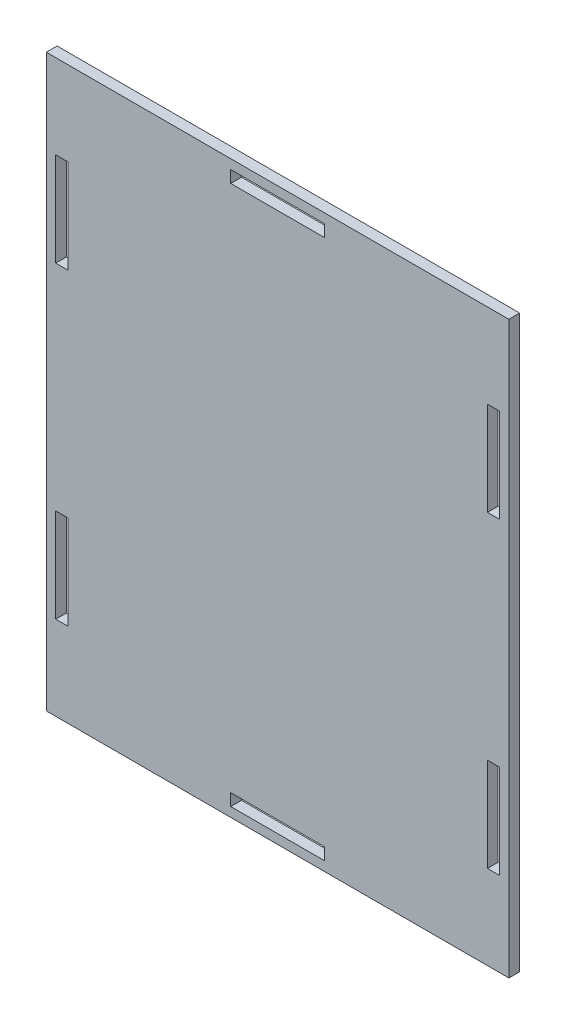
SolidWorks part; units mm, degrees
ref_plane "Спереди" through (0, 0, 0) normal (0, 0, 1) x (1, 0, 0)
ref_plane "Сверху" through (0, 0, 0) normal (0, 1, 0) x (1, 0, 0)
ref_plane "Справа" through (0, 0, 0) normal (1, 0, 0) x (0, 0, -1)
sketch "Эскиз1" plane through (0, 0, 0) normal (0, 0, 1) x (1, 0, 0)
  line L0 (75, 0) -> (75, 75.0147) construction
  line L1 (0, 0) -> (150, 0)
  line L2 (0, 0) -> (0, 185)
  line L3 (0, 185) -> (150, 185)
  line L4 (150, 0) -> (150, 185)
  line L5 (3.05, 57.7) -> (6.95, 57.7)
  line L6 (3.05, 57.7) -> (3.05, 27.3)
  line L7 (3.05, 27.3) -> (6.95, 27.3)
  line L8 (6.95, 57.7) -> (6.95, 27.3)
  line L9 (3.05, 157.7) -> (6.95, 157.7)
  line L10 (3.05, 157.7) -> (3.05, 127.3)
  line L11 (3.05, 127.3) -> (6.95, 127.3)
  line L12 (6.95, 157.7) -> (6.95, 127.3)
  line L13 (5, 127.3) -> (5, 157.7) construction
  line L14 (3.05, 142.5) -> (6.95, 142.5) construction
  line L15 (5, 27.3) -> (5, 57.7) construction
  line L16 (3.05, 42.5) -> (6.95, 42.5) construction
  line L17 (0, 92.5) -> (87.9733, 92.5) construction
  line L18 (146.95, 27.3) -> (143.05, 27.3)
  line L19 (143.05, 57.7) -> (143.05, 27.3)
  line L20 (146.95, 57.7) -> (143.05, 57.7)
  line L21 (146.95, 57.7) -> (146.95, 27.3)
  line L22 (146.95, 127.3) -> (143.05, 127.3)
  line L23 (143.05, 157.7) -> (143.05, 127.3)
  line L24 (146.95, 157.7) -> (143.05, 157.7)
  line L25 (146.95, 157.7) -> (146.95, 127.3)
  line L26 (75, 185) -> (75, 180) construction
  line L27 (59.8, 6.95) -> (90.2, 6.95)
  line L28 (59.8, 181.95) -> (90.2, 181.95)
  line L29 (59.8, 181.95) -> (59.8, 178.05)
  line L30 (59.8, 178.05) -> (90.2, 178.05)
  line L31 (90.2, 181.95) -> (90.2, 178.05)
  line L32 (59.8, 181.95) -> (90.2, 178.05) construction
  line L33 (59.8, 178.05) -> (90.2, 181.95) construction
  line L34 (90.2, 3.05) -> (90.2, 6.95)
  line L35 (59.8, 3.05) -> (90.2, 3.05)
  line L36 (59.8, 3.05) -> (59.8, 6.95)
  point P35 (75, 180)
  dimension "D1" = 185
  dimension "D2" = 150
  dimension "D3" = 30.4
  dimension "D4" = 3.9
  dimension "D5" = 5
  dimension "D6" = 30.4
  dimension "D7" = 3.9
  dimension "D8" = 50
  dimension "D9" = 50
  dimension "D10" = 5
  dimension "D11" = 5
  dimension "D12" = 30.4
  dimension "D13" = 3.9
extrude "Бобышка-Вытянуть1" add sketch "Эскиз1" along normal blind 3.5
